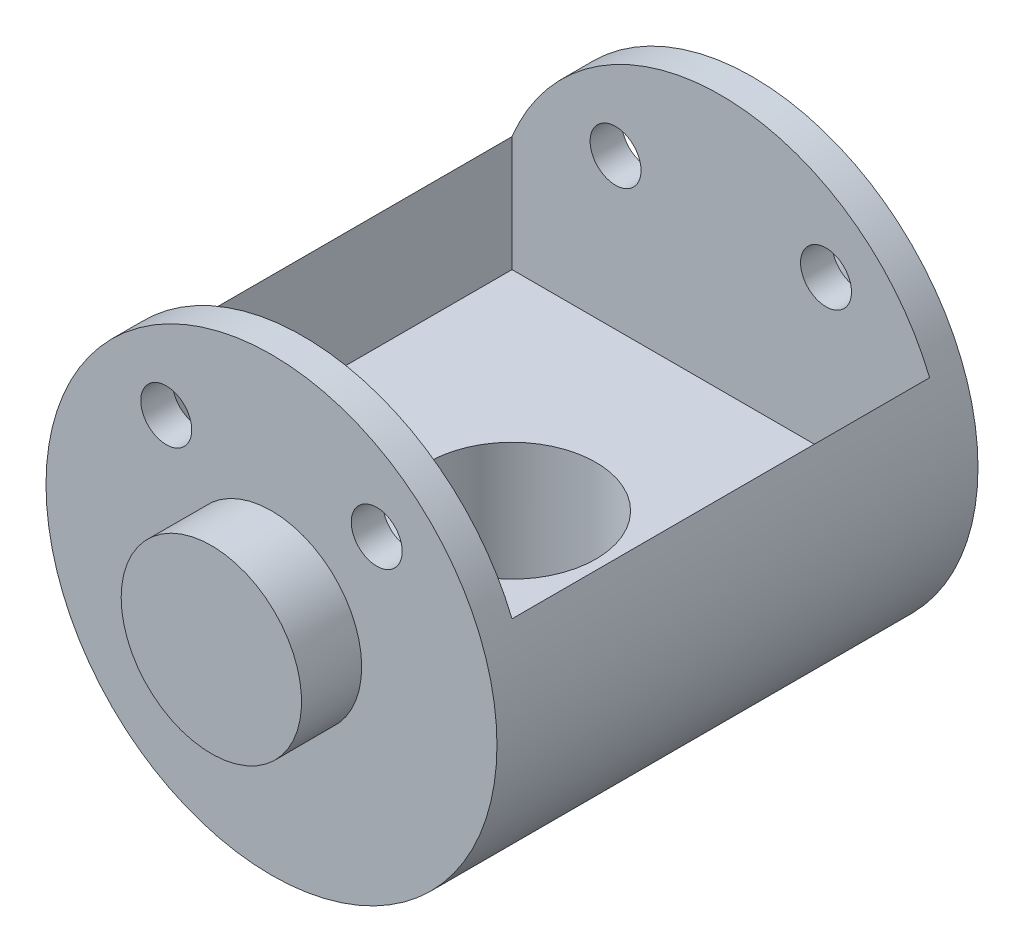
SolidWorks part; units mm, degrees
material "ABS"
ref_plane "Front Plane" through (0, 0, 0) normal (0, 0, 1) x (1, 0, 0)
ref_plane "Top Plane" through (0, 0, 0) normal (0, 1, 0) x (1, 0, 0)
ref_plane "Right Plane" through (0, 0, 0) normal (1, 0, 0) x (0, 0, -1)
sketch "Sketch2" plane through (0, 0, 0) normal (0, 0, 1) x (1, 0, 0)
  circle A0 centre (0, 0) radius 19.05
  dimension "D1" = 38.1
extrude "Extrude1" add sketch "Sketch2" along normal mid plane 40.64
sketch "Sketch3" plane through (0, 0, 20.32) normal (0, 0, 1) x (1, 0, 0)
  line L0 (0, 0) -> (0, 19.05) construction
  circle A0 centre (0, 0) radius 19.05 construction
ref_plane "Plane1" through (0, 19.05, 20.32) normal (0, 1, 0) x (-1, 0, 0)
sketch "Sketch4" plane through (0, 19.05, 20.32) normal (0, 1, 0) x (-1, 0, 0)
  line L2 (17.6403, -37.9603) -> (-17.6403, -37.9603)
  line L3 (17.6403, -37.9603) -> (17.6403, -2.6797)
  line L4 (17.6403, -2.6797) -> (-17.6403, -2.6797)
  line L5 (-17.6403, -37.9603) -> (-17.6403, -2.6797)
  line L6 (17.6403, -37.9603) -> (-17.6403, -2.6797) construction
  line L7 (17.6403, -2.6797) -> (-17.6403, -37.9603) construction
  point P3 (0, -20.32)
  dimension "D1" = 35.2806
  dimension "D2" = 35.2806
extrude "Extrude2" cut sketch "Sketch4" against normal blind 21.59
sketch "Sketch5" plane through (0, -2.54, 0) normal (0, 1, 0) x (1, 0, 0)
  circle A0 centre (0, 0) radius 7.0866
  dimension "D1" = 14.1732
extrude "Extrude3" cut sketch "Sketch5" against normal through all
sketch "Sketch7" plane through (0, 0, -20.32) normal (0, 0, -1) x (-1, 0, 0)
  circle A0 centre (0, 0) radius 7.62
  dimension "D1" = 15.24
extrude "Extrude4" add sketch "Sketch7" along normal blind 5.08
mirror "Mirror1" about plane through (0, 0, 0) normal (0, 0, 1) of "Extrude4"
sketch "Sketch8" plane through (0, 0, -20.32) normal (0, 0, -1) x (-1, 0, 0)
  line L0 (0, 0) -> (0, 10.16) construction
  line L1 (0, 10.16) -> (8.89, 10.16) construction
  line L2 (0, 10.16) -> (-8.89, 10.16) construction
  dimension "D1" = 8.89
  dimension "D2" = 10.16
hole_wizard "#8 Clearance Hole1" positions "Sketch10" profile "Sketch9" hole size "#8" standard "Ansi Inch" end condition through all
sketch "Sketch10" plane through (0, 0, -20.32) normal (0, 0, -1) x (-1, 0, 0)
  point P1 (-8.89, 10.16)
  point P4 (8.89, 10.16)
sketch "Sketch9" plane through (8.89, 10.16, -20.32) normal (1, 0, 0) x (0, 1, 0)
  line L0 (0, 0) -> (0, 45.72)
  line L1 (0, 45.72) -> (2.1526, 45.72)
  line L2 (2.1526, 45.72) -> (2.1526, 0)
  line L5 (2.1526, 0) -> (0, 0)
  line L11 (0, -6.35) -> (0, 107.95) construction
  dimension "Thru Hole Dia." = 4.3053
  dimension "Thru Hole Depth" = 45.72
